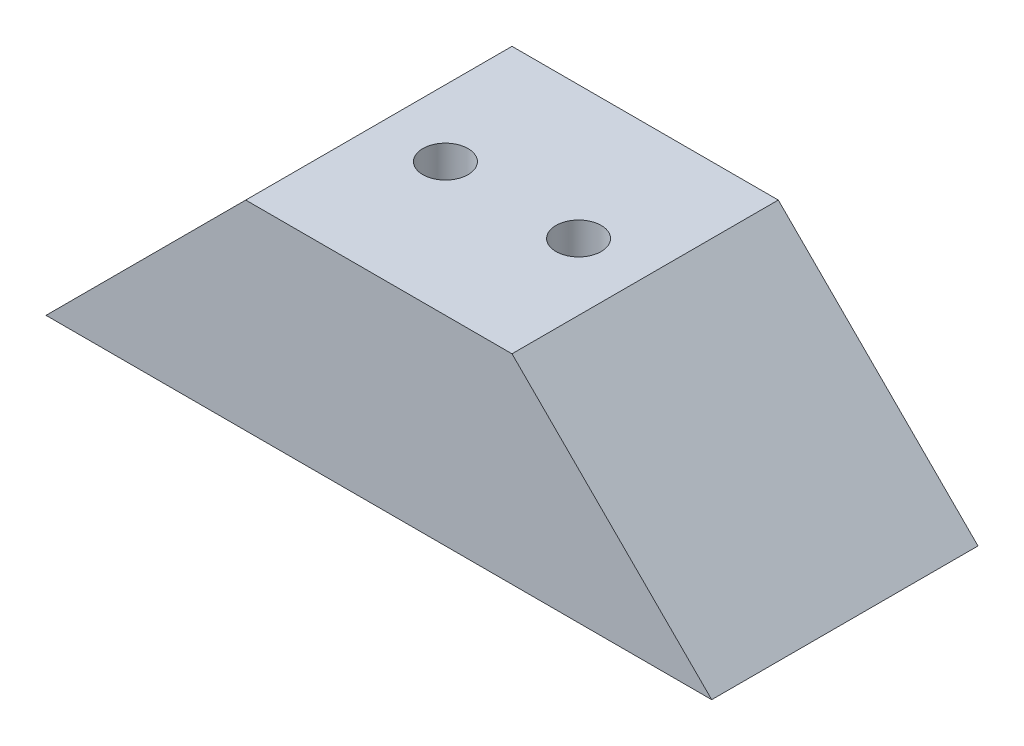
SolidWorks part; units mm, degrees
ref_plane "前视基准面" through (0, 0, 0) normal (0, 0, 1) x (1, 0, 0)
ref_plane "上视基准面" through (0, 0, 0) normal (0, 1, 0) x (1, 0, 0)
ref_plane "右视基准面" through (0, 0, 0) normal (1, 0, 0) x (0, 0, -1)
sketch "草图1" plane through (0, 0, 0) normal (0, 0, 1) x (1, 0, 0)
  line L0 (10, 7.5) -> (25, -7.5)
  line L1 (-10, -7.5) -> (10, -7.5)
  line L2 (-10, -7.5) -> (-10, 7.5) construction
  line L3 (-10, 7.5) -> (10, 7.5)
  line L4 (10, -7.5) -> (10, 7.5) construction
  line L5 (-10, -7.5) -> (10, 7.5) construction
  line L6 (-10, 7.5) -> (10, -7.5) construction
  line L7 (25, -7.5) -> (10, -7.5)
  line L8 (0, 0) -> (0, 50000) construction
  line L9 (-25, -7.5) -> (-10, -7.5)
  line L10 (-10, 7.5) -> (-25, -7.5)
  point P0 (0, 0)
  dimension "D1" = 15
  dimension "D2" = 20
  dimension "D3" = 45
extrude "凸台-拉伸1" add sketch "草图1" along normal blind 20
sketch "草图2" plane through (0, 7.5, 0) normal (0, 1, 0) x (1, 0, 0)
  line L0 (0, 0) -> (0, -50000) construction
  line L1 (10, 0) -> (-10, 0) construction
  circle A0 centre (-5, -10) radius 1.7
  circle A1 centre (5, -10) radius 1.7
  dimension "D1" = 3.4
  dimension "D2" = 10
  dimension "D3" = 10
extrude "切除-拉伸1" cut sketch "草图2" against normal through all
